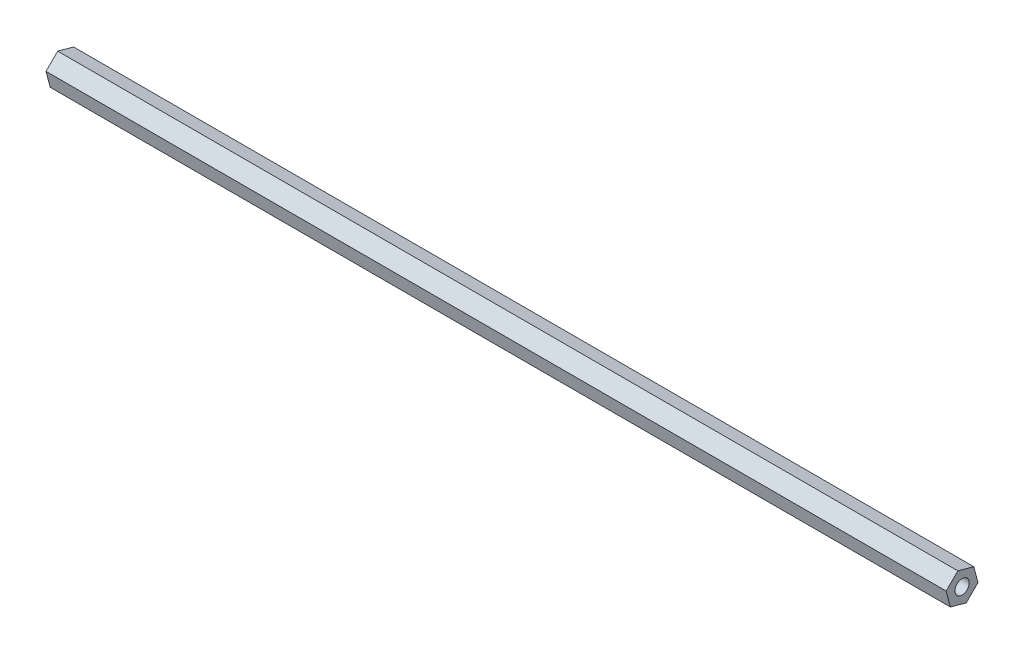
SolidWorks part; units mm, degrees
ref_plane "Front Plane" through (0, 0, 0) normal (0, 0, 1) x (1, 0, 0)
ref_plane "Top Plane" through (0, 0, 0) normal (0, 1, 0) x (1, 0, 0)
ref_plane "Right Plane" through (0, 0, 0) normal (1, 0, 0) x (0, 0, -1)
sketch "Sketch1" plane through (0, 0, 0) normal (1, 0, 0) x (0, 0, -1)
  line L1 (5.206, 5.1634) -> (-1.8687, 7.0902)
  line L2 (-1.8687, 7.0902) -> (-7.0747, 1.9268)
  line L3 (-7.0747, 1.9268) -> (-5.206, -5.1634)
  line L4 (-5.206, -5.1634) -> (1.8687, -7.0902)
  line L5 (1.8687, -7.0902) -> (7.0747, -1.9268)
  line L6 (7.0747, -1.9268) -> (5.206, 5.1634)
  dimension "D2" = 12.7
extrude "Boss-Extrude1" add sketch "Sketch1" along normal blind 400.05
sketch "Sketch2" plane through (400.05, 0, 0) normal (1, 0, 0) x (0, 0, -1)
  circle A0 centre (0, 0) radius 3.175
  dimension "D1" = 6.35
extrude "Cut-Extrude1" cut sketch "Sketch2" against normal through all
